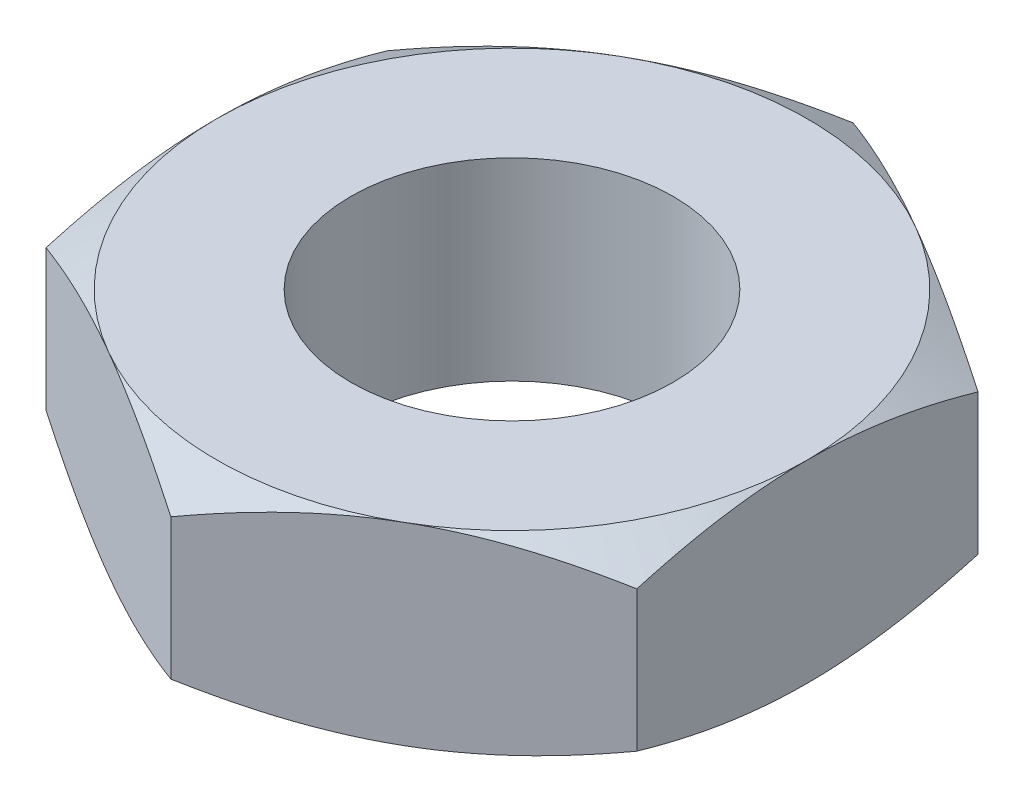
SolidWorks part; units mm, degrees
ref_plane "Front Plane" through (0, 0, 0) normal (0, 0, 1) x (1, 0, 0)
ref_plane "Top Plane" through (0, 0, 0) normal (0, 1, 0) x (1, 0, 0)
ref_plane "Right Plane" through (0, 0, 0) normal (1, 0, 0) x (0, 0, -1)
sketch "Sketch1" plane through (0, 0, 0) normal (0, 1, 0) x (1, 0, 0)
  line L1 (-2.75, 1.5877) -> (-2.75, -1.5877)
  line L2 (-2.75, -1.5877) -> (0, -3.1754)
  line L3 (0, -3.1754) -> (2.75, -1.5877)
  line L4 (2.75, -1.5877) -> (2.75, 1.5877)
  line L5 (2.75, 1.5877) -> (0, 3.1754)
  line L6 (0, 3.1754) -> (-2.75, 1.5877)
  circle A0 centre (0, 0) radius 2.75 construction
  circle A1 centre (0, 0) radius 1.5
  dimension "Thread Size" = 3
  dimension "Hex" = 5.5
extrude "Boss-Extrude1" add sketch "Sketch1" along normal mid plane 1.8
sketch "Sketch2" plane through (0, 0.9, 0) normal (0, 1, 0) x (1, 0, 0)
  circle A0 centre (0, 0) radius 1.5 construction
  circle A1 centre (0, 0) radius 1.5
sketch "Sketch5" plane through (0, 0.9, 0) normal (0, 1, 0) x (1, 0, 0)
  circle A0 centre (0, 0) radius 2.75 construction
  circle A1 centre (0, 0) radius 2.75
extrude "Cut-Extrude2" cut sketch "Sketch5" against normal through all draft 60 flip side to cut
mirror "Mirror1" about plane through (0, 0, 0) normal (0, 1, 0) of "Cut-Extrude2"
